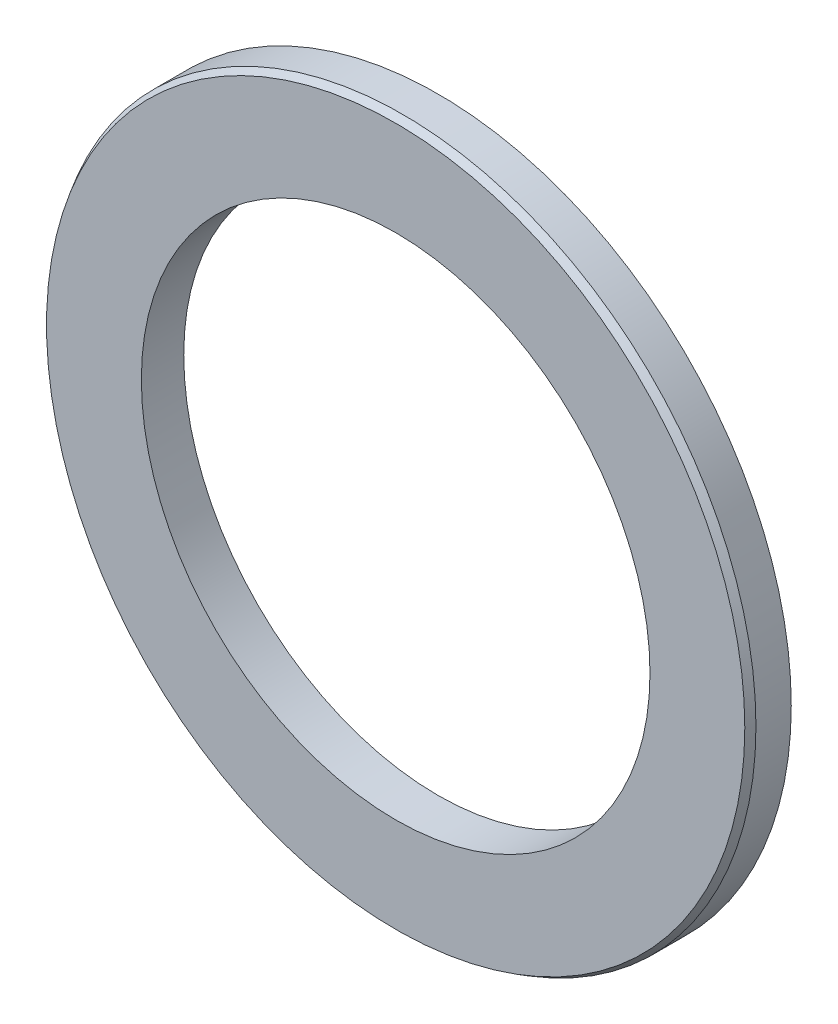
SolidWorks part; units mm, degrees
material "普通碳钢"
ref_plane "前视基准面" through (0, 0, 0) normal (0, 0, 1) x (1, 0, 0)
ref_plane "上视基准面" through (0, 0, 0) normal (0, 1, 0) x (1, 0, 0)
ref_plane "右视基准面" through (0, 0, 0) normal (1, 0, 0) x (0, 0, -1)
sketch "草图1" plane through (0, 0, 0) normal (0, 0, 1) x (1, 0, 0)
  line L0 (0, -27.9305) -> (0, 26.1225) construction
  line L1 (-29.6691, 0) -> (30.2697, 0) construction
  circle A0 centre (0, 0) radius 25
  dimension "D1" = 50
extrude "拉伸2" add sketch "草图1" along normal blind 3
sketch "草图2" plane through (0, 0, 3) normal (0, 0, 1) x (1, 0, 0)
  circle A0 centre (0, 0) radius 18
  dimension "D1" = 36
extrude "切除-拉伸1" cut sketch "草图2" against normal through all
chamfer "倒角1" distance 0.5 angle 30 1 edges at (25, 0, 3)
